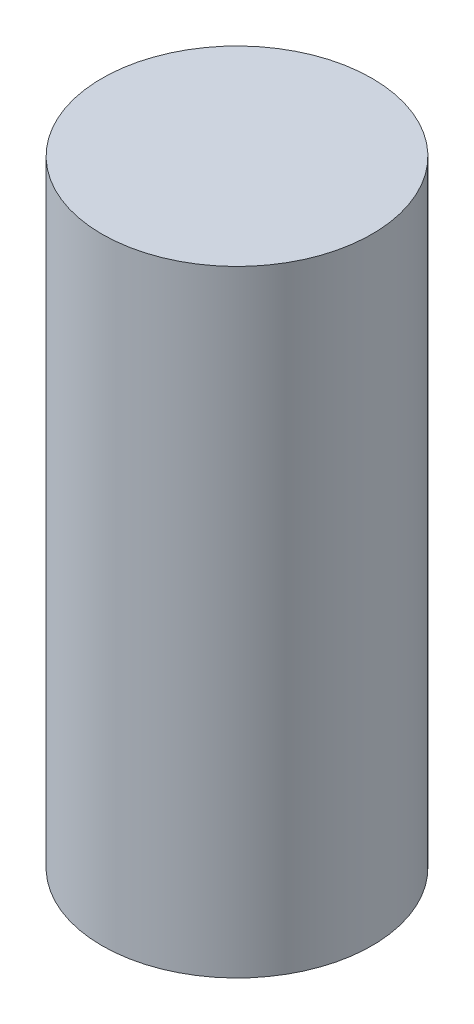
SolidWorks part; units mm, degrees
ref_plane "前视基准面" through (0, 0, 0) normal (0, 0, 1) x (1, 0, 0)
ref_plane "上视基准面" through (0, 0, 0) normal (0, 1, 0) x (1, 0, 0)
ref_plane "右视基准面" through (0, 0, 0) normal (1, 0, 0) x (0, 0, -1)
other "Configuration Table"
sketch "草图1" plane through (0, 0, 0) normal (0, 1, 0) x (1, 0, 0)
  circle A0 centre (0, 0) radius 13.585
  dimension "D1" = 27.17
extrude "凸台-拉伸1" add sketch "草图1" along normal blind 62
sketch "草图2" plane through (0, 0, 0) normal (0, 0, 1) x (1, 0, 0)
  line L0 (0, 0) -> (0, -21.5524) construction
  line L1 (-13.585, 0) -> (13.585, 0) construction
  line L3 (2.339, -6) -> (2.739, -6)
  line L10 (2.339, -6) -> (2.339, 0)
  line L11 (2.339, 0) -> (3.339, 0)
  line L12 (3.339, 0) -> (2.739, -2)
  line L13 (2.739, -2) -> (3.339, -2)
  line L14 (3.339, -2) -> (2.739, -4)
  line L15 (2.739, -4) -> (3.339, -4)
  line L16 (3.339, -4) -> (2.739, -6)
  dimension "D1" = 6
  dimension "D2" = 0.4
  dimension "D3" = 1
  dimension "D4" = 0.4
  dimension "D5" = 0.4
  dimension "D6" = 2
  dimension "D7" = 2
  dimension "D8" = 1
  dimension "D9" = 1
revolve "旋转1" add sketch "草图2" angle 360 about L0
